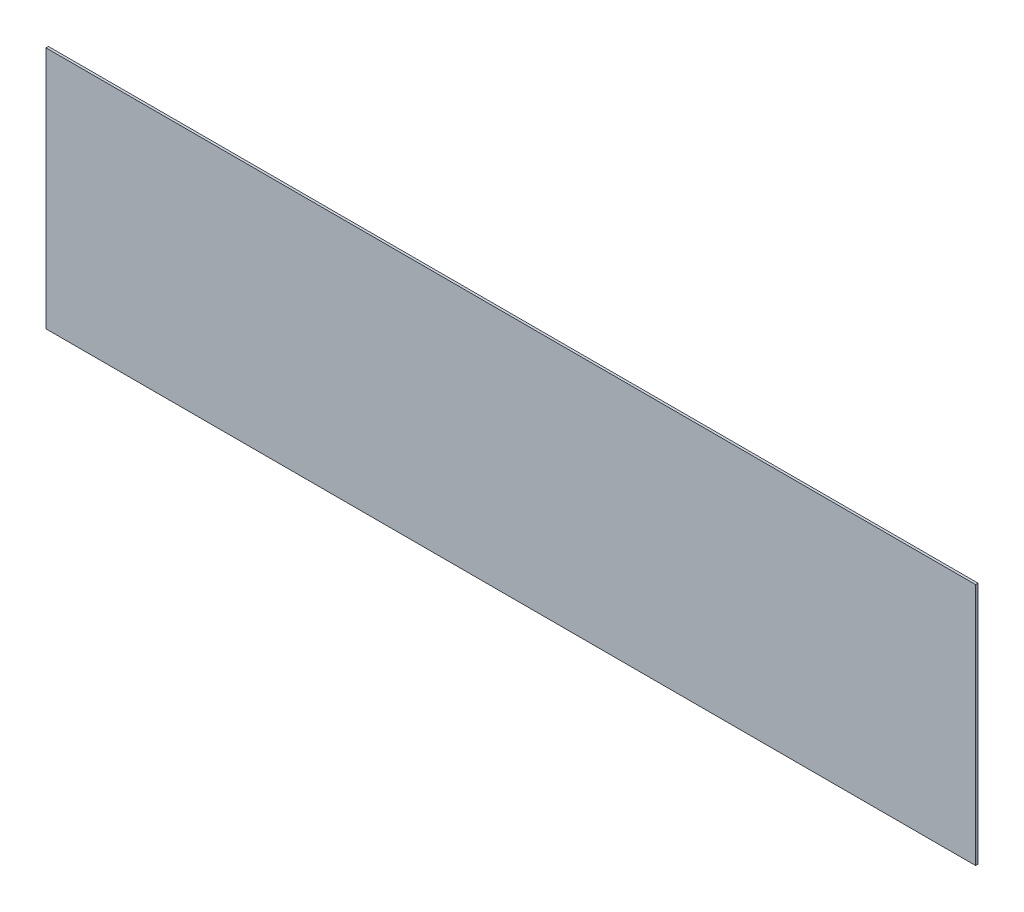
SolidWorks part; units mm, degrees
ref_plane "Front Plane" through (0, 0, 0) normal (0, 0, 1) x (1, 0, 0)
ref_plane "Top Plane" through (0, 0, 0) normal (0, 1, 0) x (1, 0, 0)
ref_plane "Right Plane" through (0, 0, 0) normal (1, 0, 0) x (0, 0, -1)
sketch "Sketch1" plane through (0, 0, 0) normal (0, 0, 1) x (1, 0, 0)
  line L1 (-189.06, 49.5) -> (189.06, 49.5)
  line L2 (-189.06, 49.5) -> (-189.06, -49.5)
  line L3 (-189.06, -49.5) -> (189.06, -49.5)
  line L4 (189.06, 49.5) -> (189.06, -49.5)
  line L5 (-189.06, 49.5) -> (189.06, -49.5) construction
  line L6 (-189.06, -49.5) -> (189.06, 49.5) construction
  point P0 (0, 0)
  dimension "D1" = 378.12
  dimension "D2" = 99
extrude "Boss-Extrude1" add sketch "Sketch1" along normal blind 1
